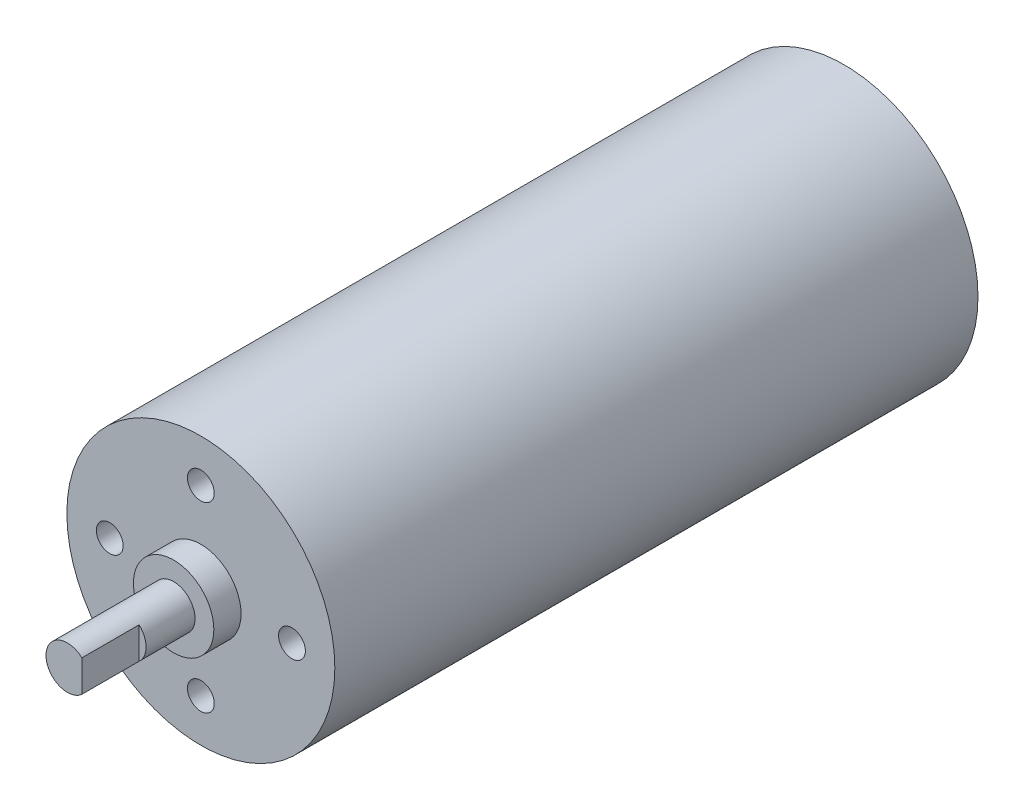
SolidWorks part; units mm, degrees
ref_plane "Front Plane" through (0, 0, 0) normal (0, 0, 1) x (1, 0, 0)
ref_plane "Top Plane" through (0, 0, 0) normal (0, 1, 0) x (1, 0, 0)
ref_plane "Right Plane" through (0, 0, 0) normal (1, 0, 0) x (0, 0, -1)
sketch "Specs" plane through (0, 0, 0) normal (0, 0, 1) x (1, 0, 0)
  line L0 (0, 12.5) -> (60, 12.5)
  line L1 (-8.5, 0) -> (8.5, 0) construction
  line L2 (0, -12.5) -> (60, -12.5)
  line L3 (-9.525, 2) -> (0, 2)
  line L4 (0, 8.5) -> (0, -8.5) construction
  line L6 (-9.525, -2) -> (0, -2)
  circle A0 centre (0, 0) radius 12.5
  circle A1 centre (60, 0) radius 12.5
  circle A2 centre (0, 0) radius 2
  circle A3 centre (0, 0) radius 3.75 construction
  circle A4 centre (0, 8.5) radius 1.65 construction
  circle A5 centre (8.5, 0) radius 1.65 construction
  circle A6 centre (0, -8.5) radius 1.65 construction
  circle A7 centre (-8.5, 0) radius 1.65 construction
  circle A8 centre (-9.525, 0) radius 2
  dimension "D2" = 3.3
  dimension "D3" = 7.5
  dimension "D4" = 4
  dimension "D5" = 25
  dimension "D1" = 17
  dimension "D6" = 60
  dimension "D7" = 9.525
sketch "Sketch1" plane through (0, 0, 0) normal (0, 0, 1) x (1, 0, 0)
  circle A0 centre (0, 0) radius 12.5
  circle A1 centre (0, 0) radius 12.5 construction
extrude "Boss-Extrude1" add sketch "Sketch1" against normal blind 60
sketch "Sketch4" plane through (0, 0, 0) normal (0, 0, 1) x (1, 0, 0)
  circle A0 centre (0, 0) radius 2
extrude "Boss-Extrude3" add sketch "Sketch4" along normal blind 12.446
sketch "Sketch5" plane through (0, 0, 0) normal (0, 0, 1) x (1, 0, 0)
  circle A0 centre (0, 0) radius 3.75
extrude "Boss-Extrude4" add sketch "Sketch5" along normal blind 2.54
sketch "Sketch6" plane through (0, 0, 12.446) normal (0, 0, 1) x (1, 0, 0)
  line L0 (1.3528, 1.4731) -> (1.3528, -1.4731)
  circle A0 centre (0, 0) radius 2 construction
  arc A1 (1.3528, 1.4731) -> (1.3528, -1.4731) centre (0, 0) cw
extrude "Cut-Extrude2" cut sketch "Sketch6" against normal blind 5.334
hole_wizard "Tap Drill for M3x0.5 Tap1" positions "Sketch8" profile "Sketch7" hole size "M3x0.5" standard "ANSI Metric"
sketch "Sketch8" plane through (0, 0, 0) normal (0, 0, 1) x (1, 0, 0)
  point P0 (0, 8.5)
  point P3 (8.5, 0)
  point P6 (0, -8.5)
  point P9 (-8.5, 0)
sketch "Sketch7" plane through (0, 8.5, 0) normal (1, 0, 0) x (0, -1, 0)
  line L0 (0, 0) -> (0, 10.7511)
  line L1 (0, 10.7511) -> (1.25, 10)
  line L2 (1.25, 10) -> (1.25, 0)
  line L5 (1.25, 0) -> (0, 0)
  line L10 (0, 10.7511) -> (-1.25, 10) construction
  line L11 (0, -6.35) -> (0, 107.95) construction
  dimension "Hole Dia." = 2.5
  dimension "Hole Depth" = 10
  dimension "Drill Angle" = 118
equation "\"D1@Boss-Extrude1\"=\"D6@Specs\""
equation "\"D1@Boss-Extrude3\"=\"D7@Specs\""
